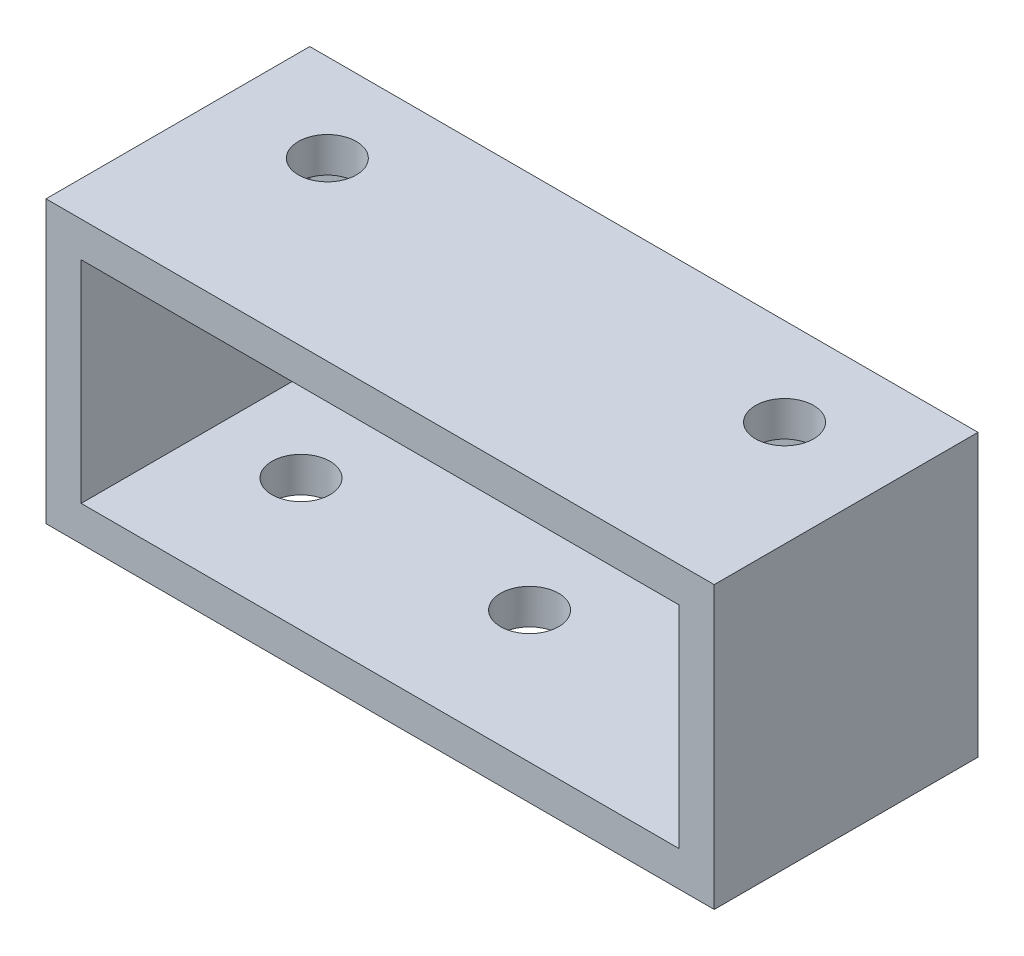
SolidWorks part; units mm, degrees
ref_plane "前视基准面" through (0, 0, 0) normal (0, 0, 1) x (1, 0, 0)
ref_plane "上视基准面" through (0, 0, 0) normal (0, 1, 0) x (1, 0, 0)
ref_plane "右视基准面" through (0, 0, 0) normal (1, 0, 0) x (0, 0, -1)
sketch "草图1" plane through (0, 0, 0) normal (0, 1, 0) x (1, 0, 0)
  line L1 (0, 0) -> (38, 0)
  line L2 (0, 0) -> (0, 15)
  line L3 (0, 15) -> (38, 15)
  line L4 (38, 0) -> (38, 15)
  dimension "D1" = 38
  dimension "D2" = 15
extrude "凸台-拉伸1" add sketch "草图1" along normal blind 16
sketch "草图2" plane through (0, 0, 0) normal (0, 0, 1) x (1, 0, 0)
  line L8 (2, 2) -> (36, 2)
  line L9 (36, 2) -> (36, 14)
  line L10 (36, 14) -> (2, 14)
  line L11 (2, 14) -> (2, 2)
  line L12 (2, 2) -> (36, 2)
  line L13 (36, 2) -> (36, 14)
  line L14 (36, 14) -> (2, 14)
  line L15 (2, 14) -> (2, 2)
  dimension "D1" = 2
extrude "切除-拉伸1" cut sketch "草图2" against normal offset from surface (13 mm away) 2 up to face at (19, 8, -15)
sketch "草图3" plane through (0, 16, 0) normal (0, 1, 0) x (1, 0, 0)
  line L0 (0, 10) -> (38, 10) construction
  line L3 (19, 15) -> (19, -2.8236) construction
  line L4 (38, 15) -> (0, 15) construction
  line L6 (2, 13) -> (36, 13) construction
  circle A0 centre (6, 10) radius 1.65
  circle A1 centre (32, 10) radius 1.65
  dimension "D1" = 3.3
  dimension "D2" = 26
  dimension "D3" = 3
extrude "切除-拉伸2" cut sketch "草图3" against normal blind 2
sketch "草图4" plane through (0, 2, 0) normal (0, 1, 0) x (1, 0, 0)
  line L0 (0, 7.5) -> (39.9529, 7.5) construction
  line L1 (2, 13) -> (2, 0) construction
  line L2 (0, 15) -> (0, 0) construction
  circle A0 centre (7, 7.5) radius 1.65
  circle A1 centre (20, 7.5) radius 1.65
  point P6 (0, 7.5)
  dimension "D1" = 3.3
  dimension "D2" = 3.3
  dimension "D3" = 13
  dimension "4" = 5
extrude "切除-拉伸3" cut sketch "草图4" against normal blind 10
